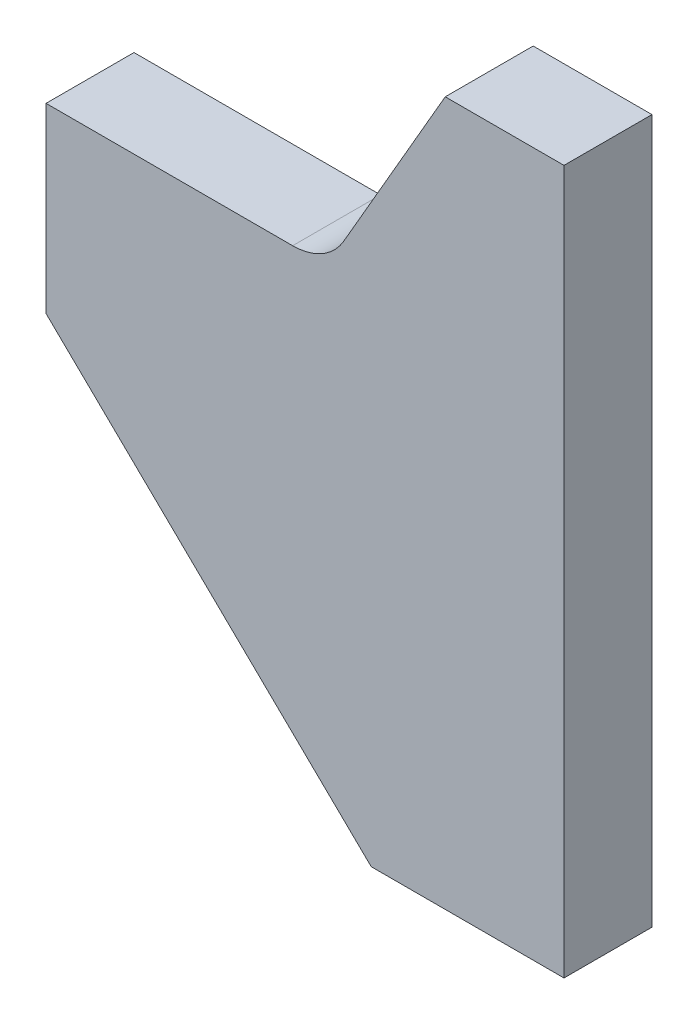
SolidWorks part; units mm, degrees
ref_plane "Front Plane" through (0, 0, 0) normal (0, 0, 1) x (1, 0, 0)
ref_plane "Top Plane" through (0, 0, 0) normal (0, 1, 0) x (1, 0, 0)
ref_plane "Right Plane" through (0, 0, 0) normal (1, 0, 0) x (0, 0, -1)
sketch "Sketch1" plane through (0, 0, 0) normal (0, 0, 1) x (1, 0, 0)
  line L0 (79.925, 13.1696) -> (86.5, 13.1696)
  line L1 (86.5, 13.1696) -> (86.5, 37.1696)
  line L2 (86.5, 37.1696) -> (82.45, 37.1696)
  line L3 (82.45, 37.1696) -> (78.9897, 31.1763)
  line L4 (77.2461, 30.1696) -> (68.8362, 30.1696)
  line L5 (67.5, 30.1696) -> (76.0991, 30.1696) construction
  line L6 (79.5632, 32.1696) -> (82.1613, 36.6696) construction
  line L7 (83.0273, 37.1696) -> (85, 37.1696) construction
  line L8 (86.5, 35.6696) -> (86.5, 18.6994) construction
  line L9 (79.5, 13.1696) -> (85, 13.1696) construction
  line L10 (79.925, 13.1696) -> (68.8362, 23.962)
  line L11 (68.8362, 30.1696) -> (68.8362, 23.962)
  arc A0 (78.9897, 31.1763) -> (77.2461, 30.1696) centre (77.2461, 32.183) cw
extrude "Boss-Extrude1" add sketch "Sketch1" along normal blind 3 contours L10 L11 L4 A0 L3 L2 L1 L0
